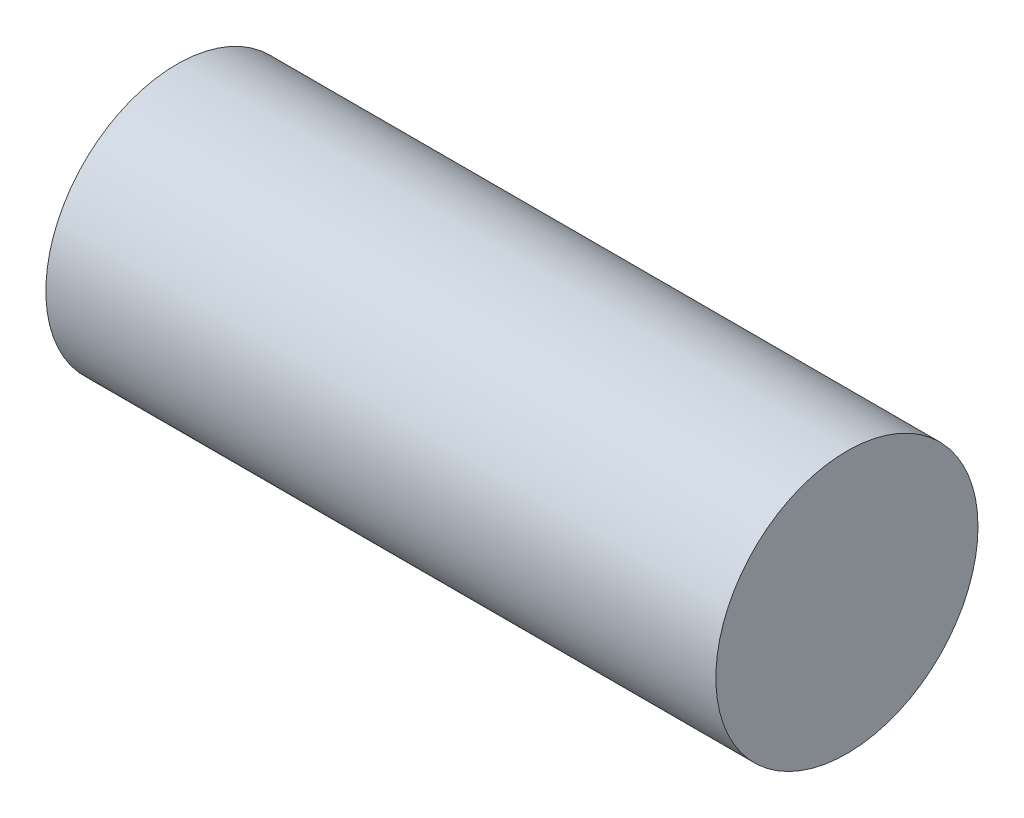
SolidWorks part; units mm, degrees
ref_plane "Front Plane" through (0, 0, 0) normal (1, 0, 0) x (0, 1, 0)
ref_plane "Top Plane" through (0, 0, 0) normal (0, 0, 1) x (0, 1, 0)
ref_plane "Right Plane" through (0, 0, 0) normal (0, 1, 0) x (-1, 0, 0)
sketch "Sketch1" plane through (0, 0, 0) normal (1, 0, 0) x (0, 1, 0)
  circle A0 centre (0, 0) radius 7.825
  dimension "D1" = 15.65
extrude "Boss-Extrude1" add sketch "Sketch1" along normal blind 40 contours A0
